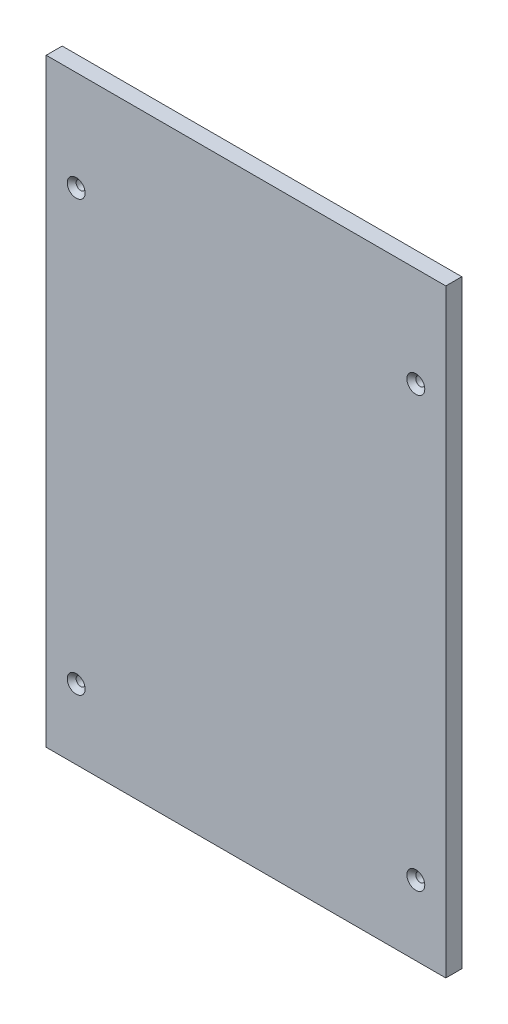
SolidWorks part; units mm, degrees
ref_plane "Plano frontal" through (0, 0, 0) normal (0, 0, 1) x (1, 0, 0)
ref_plane "Plano superior" through (0, 0, 0) normal (0, 1, 0) x (1, 0, 0)
ref_plane "Plano direito" through (0, 0, 0) normal (1, 0, 0) x (0, 0, -1)
sketch "Esboço1" plane through (0, 0, 0) normal (0, 0, 1) x (1, 0, 0)
  line L1 (0, 0) -> (200, 0)
  line L2 (0, 0) -> (0, 300)
  line L3 (0, 300) -> (200, 300)
  line L4 (200, 0) -> (200, 300)
  dimension "D1" = 300
  dimension "D2" = 200
extrude "Ressalto-extrusão1" add sketch "Esboço1" along normal blind 8
sketch "Esboço2" plane through (0, 0, 8) normal (0, 0, 1) x (1, 0, 0)
  line L0 (0, 250) -> (200, 250) construction
  line L1 (0, 300) -> (0, 0) construction
  line L2 (200, 0) -> (200, 300) construction
  line L3 (0, 35) -> (200, 35) construction
  line L4 (15, 300) -> (15, 0) construction
  line L5 (200, 300) -> (0, 300) construction
  line L6 (185, 300) -> (185, 0) construction
  line L7 (0, 0) -> (200, 0) construction
  point P16 (15, 250)
  point P17 (185, 250)
  point P18 (185, 35)
  point P19 (15, 35)
  dimension "D1" = 15
  dimension "D2" = 50
  dimension "D3" = 35
  dimension "D4" = 15
hole_wizard "Escareado para SFHCS M41" positions "3DSketch1" profile "Esboço3" countersink size "M4" standard "Ansi Metric" end condition through all
sketch3d "3DSketch1"
  point P0 (15, 250, 8)
  point P3 (185, 250, 8)
  point P6 (15, 35, 8)
  point P9 (185, 35, 8)
sketch "Esboço3" plane through (15, 250, 8) normal (1, 0, 0) x (0, -1, 0)
  line L0 (0, 0) -> (0, 8)
  line L1 (0, 8) -> (2.25, 8)
  line L2 (2.25, 8) -> (2.25, 2.23)
  line L3 (2.25, 2.23) -> (4.48, 0)
  line L5 (4.48, 0) -> (0, 0)
  line L6 (-2.25, 2.23) -> (-4.48, 0) construction
  line L11 (0, -6.35) -> (0, 107.95) construction
  dimension "Thru Hole Dia." = 4.5
  dimension "Thru Hole Depth" = 8
  dimension "Near C'Sink Dia." = 8.96
  dimension "Near C'Sink Angle" = 90
